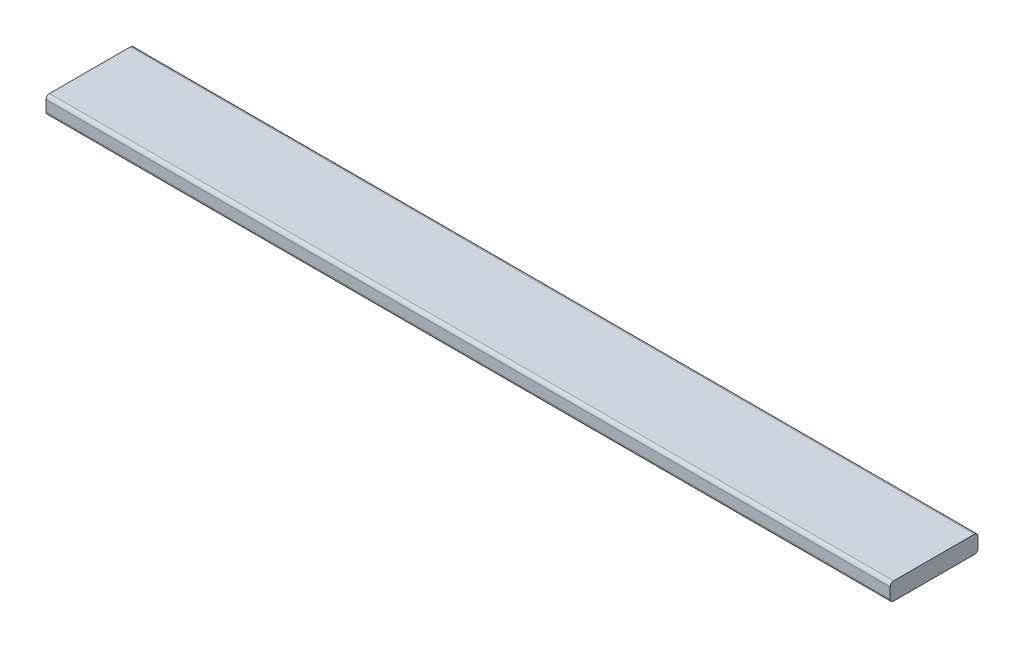
SolidWorks part; units mm, degrees
ref_plane "Front Plane" through (0, 0, 0) normal (0, 0, 1) x (1, 0, 0)
ref_plane "Top Plane" through (0, 0, 0) normal (0, 1, 0) x (1, 0, 0)
ref_plane "Right Plane" through (0, 0, 0) normal (1, 0, 0) x (0, 0, -1)
sketch "Sketch1" plane through (0, 0, 0) normal (0, 1, 0) x (1, 0, 0)
  line L1 (152.4, -15.875) -> (-152.4, -15.875)
  line L2 (152.4, -15.875) -> (152.4, 15.875)
  line L3 (152.4, 15.875) -> (-152.4, 15.875)
  line L4 (-152.4, -15.875) -> (-152.4, 15.875)
  line L5 (152.4, -15.875) -> (-152.4, 15.875) construction
  line L6 (152.4, 15.875) -> (-152.4, -15.875) construction
  point P0 (0, 0)
  dimension "D1" = 31.75
  dimension "D2" = 304.8
extrude "Boss-Extrude1" add sketch "Sketch1" along normal blind 6.35
fillet "Fillet1" radius 1.27 4 edges at (0, 0, -15.875) (0, 6.35, -15.875) (0, 0, 15.875) (0, 6.35, 15.875)
